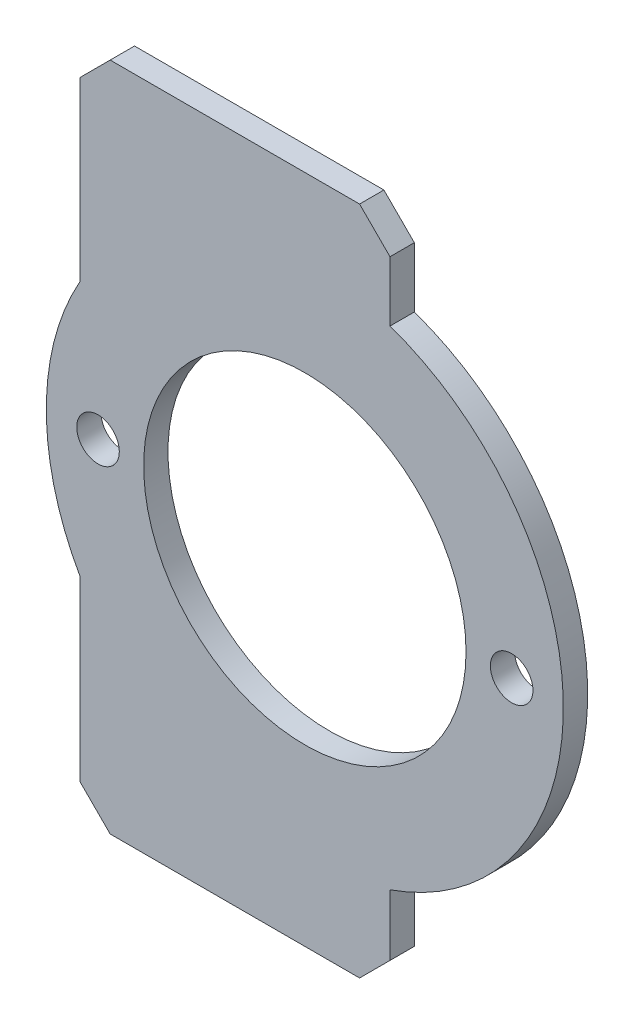
SolidWorks part; units mm, degrees
ref_plane "Front Plane" through (0, 0, 0) normal (0, 0, 1) x (1, 0, 0)
ref_plane "Top Plane" through (0, 0, 0) normal (0, 1, 0) x (1, 0, 0)
ref_plane "Right Plane" through (0, 0, 0) normal (1, 0, 0) x (0, 0, -1)
sketch "Sketch1" plane through (0, 0, 0) normal (0, 0, 1) x (1, 0, 0)
  circle A0 centre (0, 0) radius 26.5
  circle A1 centre (0, 0) radius 42.5
  circle A2 centre (34, 0) radius 3.5
  circle A3 centre (-34, 0) radius 3.5
  dimension "D1" = 53
  dimension "D2" = 85
  dimension "D3" = 7
  dimension "D4" = 7
  dimension "D6" = 34
  dimension "D5" = 34
extrude "Boss-Extrude1" add sketch "Sketch1" against normal blind 4
sketch "Sketch2" plane through (0, 0, 0) normal (0, 0, 1) x (1, 0, 0)
  line L0 (-37, 55) -> (-37, 20.9105)
  line L2 (-37, 20.9105) -> (14, 40.1279)
  line L3 (14, 40.1279) -> (14, 55)
  line L4 (14, 55) -> (-37, 55)
  line L5 (-37, -55.1883) -> (-37, -20.9105)
  line L6 (-37, -20.9105) -> (14, -40.1279)
  line L7 (14, -40.1279) -> (14, -55.1883)
  line L8 (14, -55.1883) -> (-37, -55.1883)
  circle A0 centre (0, 0) radius 42.5 construction
  circle A2 centre (0.263, -0.1883) radius 31.75 construction
  circle A3 centre (0, 0) radius 31.5 construction
  circle A4 centre (0, 0) radius 26.5 construction
  dimension "D1" = 55
  dimension "D3" = 14
  dimension "D4" = 14
  dimension "D2" = 55
  dimension "D5" = 37
extrude "Boss-Extrude2" add sketch "Sketch2" against normal blind 4
chamfer "Chamfer1" distance 5 angle 45 4 edges at (14, -55.1883, -2) (-37, -55.1883, -2) (14, 55, -2) (-37, 55, -2)
